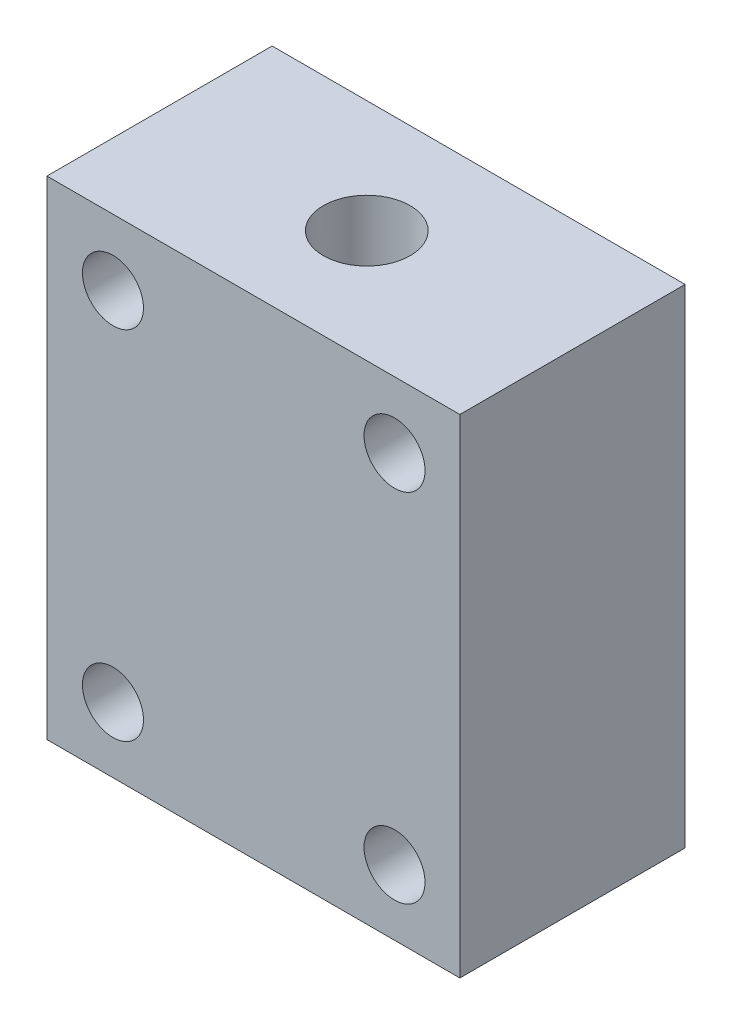
SolidWorks part; units mm, degrees
ref_plane "Front Plane" through (0, 0, 0) normal (1, 0, 0) x (0, 1, 0)
ref_plane "Top Plane" through (0, 0, 0) normal (0, 0, 1) x (0, 1, 0)
ref_plane "Right Plane" through (0, 0, 0) normal (0, 1, 0) x (-1, 0, 0)
sketch "Sketch1" plane through (0, 0, 0) normal (0, 0, 1) x (0, 1, 0)
  line L1 (-41.275, -34.925) -> (41.275, -34.925)
  line L2 (-41.275, -34.925) -> (-41.275, 34.925)
  line L3 (-41.275, 34.925) -> (41.275, 34.925)
  line L4 (41.275, -34.925) -> (41.275, 34.925)
  line L5 (-41.275, -34.925) -> (41.275, 34.925) construction
  line L6 (-41.275, 34.925) -> (41.275, -34.925) construction
  point P0 (0, 0)
extrude "Boss-Extrude1" add sketch "Sketch1" along normal mid plane 38.1
sketch "Sketch2" plane through (0, 0, 0) normal (0, 0, 1) x (0, 1, 0)
  circle A0 centre (-30.226, -23.876) radius 5.1594
extrude "Cut-Extrude2" cut sketch "Sketch2" along normal up to next from offset 19.05
sketch "Sketch3" plane through (0, 0, 0) normal (0, 0, 1) x (0, 1, 0)
  circle A0 centre (30.099, -23.876) radius 5.1594
  circle A1 centre (-30.226, 23.749) radius 5.1594
  circle A2 centre (30.099, 23.749) radius 5.1594
extrude "Cut-Extrude4" cut sketch "Sketch3" along normal up to next from offset 19.05
sketch "Sketch4" plane through (0, 0, 0) normal (0, 0, 1) x (0, 1, 0)
  circle A0 centre (-17.653, -0.127) radius 7.3422
extrude "Cut-Extrude6" cut sketch "Sketch4" along normal blind 28.448 from offset 19.05
sketch "Sketch5" plane through (0, 0, 0) normal (0, 0, 1) x (0, 1, 0)
  circle A0 centre (-17.653, -0.127) radius 12.7254
extrude "Cut-Extrude8" cut sketch "Sketch5" along normal blind 2.8194 from offset 19.05
sketch "Sketch6" plane through (0, 0, 0) normal (0, 0, 1) x (0, 1, 0)
  circle A0 centre (17.399, -0.127) radius 7.3422
extrude "Cut-Extrude10" cut sketch "Sketch6" along normal blind 28.448 from offset 19.05
sketch "Sketch7" plane through (0, 0, 0) normal (0, 0, 1) x (0, 1, 0)
  circle A0 centre (17.399, -0.127) radius 12.7254
extrude "Cut-Extrude12" cut sketch "Sketch7" along normal blind 2.8194 from offset 19.05
sketch "Sketch8" plane through (0, 0, 0) normal (0, 1, 0) x (-1, 0, 0)
  circle A0 centre (-0.127, 0) radius 7.3422
extrude "Cut-Extrude14" cut sketch "Sketch8" against normal blind 60.452 from offset 41.275
